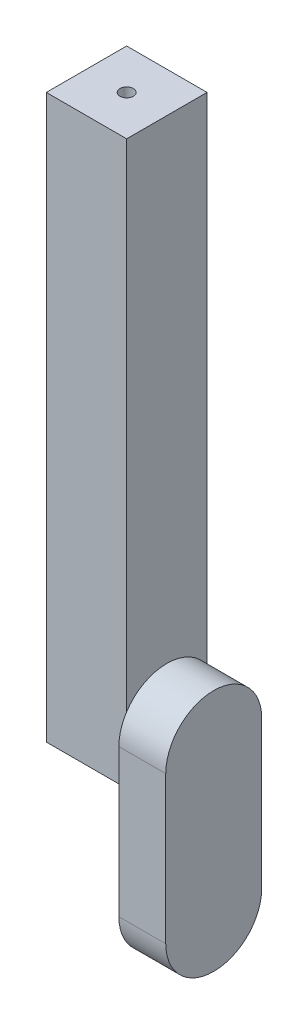
SolidWorks part; units mm, degrees
ref_plane "Front Plane" through (0, 0, 0) normal (0, 0, 1) x (1, 0, 0)
ref_plane "Top Plane" through (0, 0, 0) normal (0, 1, 0) x (1, 0, 0)
ref_plane "Right Plane" through (0, 0, 0) normal (1, 0, 0) x (0, 0, -1)
sketch "Sketch1" plane through (0, 0, 0) normal (0, 1, 0) x (1, 0, 0)
  line L1 (-30, 30) -> (30, 30)
  line L2 (-30, 30) -> (-30, -30)
  line L3 (-30, -30) -> (30, -30)
  line L4 (30, 30) -> (30, -30)
  line L5 (-30, 30) -> (30, -30) construction
  line L6 (-30, -30) -> (30, 30) construction
  point P0 (0, 0)
  dimension "D1" = 60
  dimension "D2" = 60
extrude "Boss-Extrude1" add sketch "Sketch1" along normal blind 500
sketch "Sketch2" plane through (30, 0, 0) normal (1, 0, 0) x (0, 0, -1)
  circle A0 centre (0, 0) radius 12.5
extrude "Boss-Extrude6" add sketch "Sketch2" along normal blind 2.5 and the other way blind 30
sketch "Sketch5" plane through (30, 0, 0) normal (1, 0, 0) x (0, 0, -1)
  line L0 (30, 500) -> (30, 0) construction
  line L2 (-30, 0) -> (-30, 80)
  line L3 (-30, 80) -> (30, 80)
  line L4 (30, 0) -> (30, 80)
  line L9 (-30, 0) -> (-12.5, 0)
  line L10 (12.5, 0) -> (30, 0)
  arc A0 (12.5, 0) -> (-12.5, 0) centre (0, 0) ccw
  point P0 (0, 0)
extrude "Cut-Extrude1" cut sketch "Sketch5" against normal through all
sketch "Sketch6" plane through (30, 0, 0) normal (1, 0, 0) x (0, 0, -1)
  line L0 (0, 0) -> (0, 110) construction
  line L1 (0, 110) -> (0, 0) construction
  line L2 (35.8198, 110) -> (35.8198, 0)
  line L3 (-35.8198, 110) -> (-35.8198, 0)
  arc A0 (35.8198, 110) -> (-35.8198, 110) centre (0, 110) ccw
  arc A1 (-35.8198, 0) -> (35.8198, 0) centre (0, 0) ccw
  point P3 (0, 55)
  dimension "D1" = 110
extrude "Boss-Extrude7" add sketch "Sketch6" along normal blind 35
sketch "Sketch7" plane through (0, 0, 0) normal (0, -1, 0) x (1, 0, 0)
  line L4 (0, -12.5) -> (0, 12.5)
  line L5 (0, 12.5) -> (-30, 12.5)
  line L6 (-30, 12.5) -> (-30, -12.5)
  line L7 (-30, -12.5) -> (0, -12.5)
  line L8 (0, -12.5) -> (0, 12.5)
  line L9 (0, 12.5) -> (-30, 12.5)
  line L10 (-30, 12.5) -> (-30, -12.5)
  line L11 (-30, -12.5) -> (0, -12.5)
  dimension "D1" = 0
extrude "Cut-Extrude2" cut sketch "Sketch7" against normal blind 15
sketch "Sketch8" plane through (0, 0, 0) normal (-1, 0, 0) x (0, 0, 1)
  circle A1 centre (0, 0) radius 12.5
  circle A2 centre (0, 0) radius 12.5
  dimension "D1" = 0
extrude "Cut-Extrude3" cut sketch "Sketch8" against normal blind 22.5
sketch "Sketch9" plane through (0, 500, 0) normal (0, 1, 0) x (1, 0, 0)
  point P0 (0, 0)
sketch "Sketch10" plane through (0, 500, 0) normal (0, 1, 0) x (1, 0, 0)
  circle A0 centre (0, 0) radius 5
extrude "Cut-Extrude4" cut sketch "Sketch10" against normal blind 20
